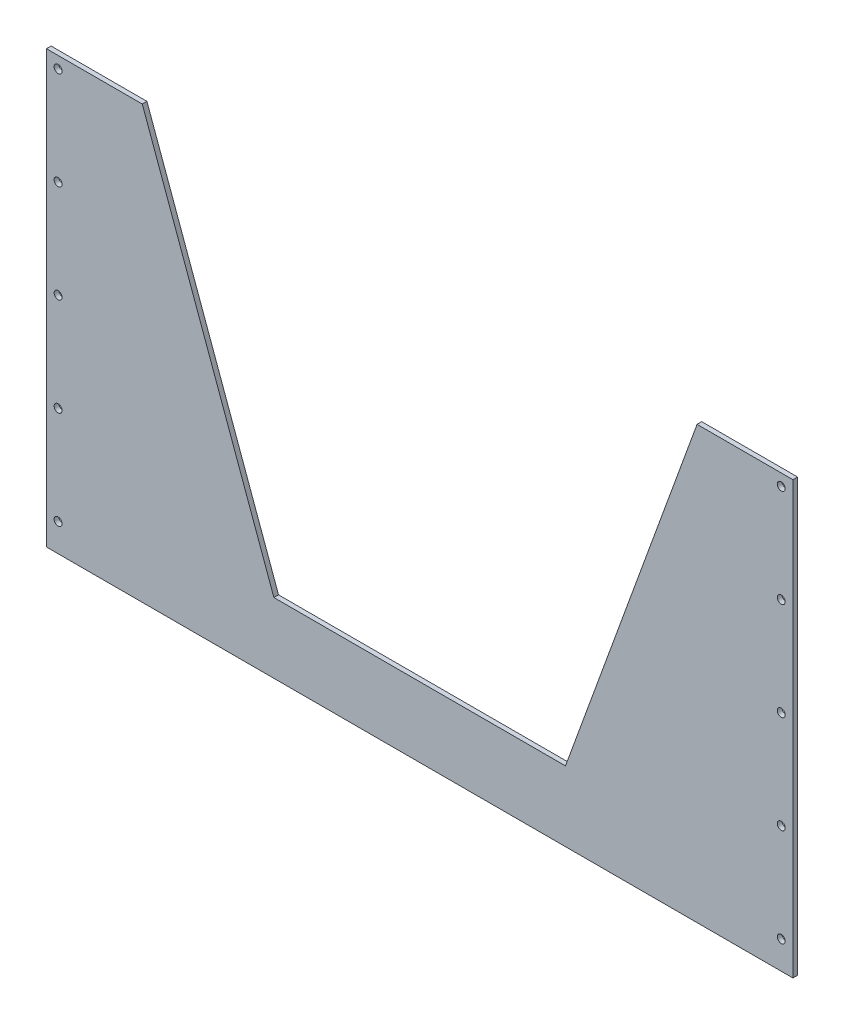
SolidWorks part; units mm, degrees
ref_plane "Спереди" through (0, 0, 0) normal (0, 0, 1) x (1, 0, 0)
ref_plane "Сверху" through (0, 0, 0) normal (0, 1, 0) x (1, 0, 0)
ref_plane "Справа" through (0, 0, 0) normal (1, 0, 0) x (0, 0, -1)
sketch "Эскиз1" plane through (0, 0, 0) normal (0, 0, 1) x (1, 0, 0)
  line L0 (-118.9154, 92.5) -> (-62.5, -62.5)
  line L1 (-160, 92.5) -> (-118.9154, 92.5)
  line L2 (-160, 92.5) -> (-160, -92.5)
  line L3 (-160, -92.5) -> (160, -92.5)
  line L4 (160, 92.5) -> (160, -92.5)
  line L5 (0, -92.5) -> (0, 97) construction
  line L6 (-160, 0) -> (160, 0) construction
  line L7 (-62.5, -62.5) -> (62.5, -62.5)
  line L8 (62.5, -62.5) -> (118.9154, 92.5)
  line L9 (118.9154, 92.5) -> (160, 92.5)
  point P0 (0, 0)
  point P7 (0, -62.5)
  dimension "D1" = 320
  dimension "D2" = 185
  dimension "D3" = 110
  dimension "D4" = 110
  dimension "D5" = 125
  dimension "D6" = 30
extrude "Бобышка-Вытянуть1" add sketch "Эскиз1" along normal mid plane 2
sketch "Эскиз2" plane through (0, 0, 1) normal (0, 0, 1) x (1, 0, 0)
  line L0 (-160, 92.5) -> (-160, -92.5) construction
  line L1 (-118.9154, 92.5) -> (-160, 92.5) construction
  line L2 (0, 50.4064) -> (0, -142.4253) construction
  circle A0 centre (-155, 87.5) radius 1.7
  circle A1 centre (-155, 45.5) radius 1.7
  circle A2 centre (-155, 3.5) radius 1.7
  circle A3 centre (-155, -38.5) radius 1.7
  circle A4 centre (-155, -80.5) radius 1.7
  circle A5 centre (155, -80.5) radius 1.7
  circle A6 centre (155, -38.5) radius 1.7
  circle A7 centre (155, 3.5) radius 1.7
  circle A8 centre (155, 45.5) radius 1.7
  circle A9 centre (155, 87.5) radius 1.7
  dimension "D1" = 3.4
  dimension "D2" = 5
  dimension "D3" = 5
  dimension "D4" = 5
extrude "Вырез-Вытянуть1" cut sketch "Эскиз2" against normal blind 10
